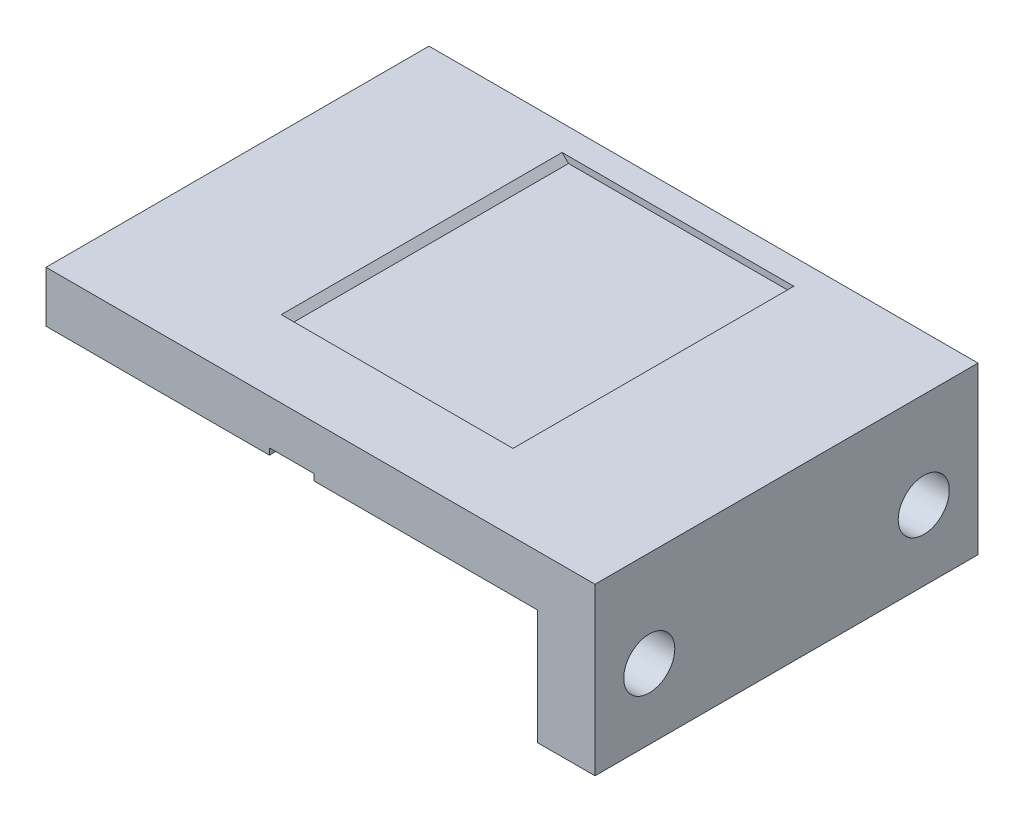
SolidWorks part; units mm, degrees
ref_plane "Front Plane" through (0, 0, 0) normal (0, 0, 1) x (1, 0, 0)
ref_plane "Top Plane" through (0, 0, 0) normal (0, 1, 0) x (1, 0, 0)
ref_plane "Right Plane" through (0, 0, 0) normal (1, 0, 0) x (0, 0, -1)
sketch "Sketch1" plane through (0, 0, 0) normal (0, 1, 0) x (1, 0, 0)
  line L1 (0, 0) -> (77, 0)
  line L2 (0, 0) -> (0, 60)
  line L3 (0, 60) -> (77, 60)
  line L4 (77, 0) -> (77, 60)
  dimension "D1" = 77
  dimension "D2" = 60
extrude "Boss-Extrude1" add sketch "Sketch1" along normal blind 8
sketch "Sketch3" plane through (77, 0, 0) normal (1, 0, 0) x (0, 0, -1)
  line L0 (60, 8) -> (60, 0) construction
  line L1 (0, 8) -> (60, 8)
  line L2 (0, 8) -> (0, -18)
  line L3 (0, -18) -> (60, -18)
  line L4 (60, 8) -> (60, -18)
  dimension "D1" = 26
extrude "Boss-Extrude2" add sketch "Sketch3" along normal blind 9 contours L2 L3 L4 L1
sketch "Sketch4" plane through (86, 0, 0) normal (1, 0, 0) x (0, 0, -1)
  line L0 (0, 8) -> (60, 8) construction
  line L1 (30, 8) -> (30, -18) construction
  line L2 (0, -18) -> (60, -18) construction
  line L5 (0, 8) -> (0, -18) construction
  line L6 (17, -7) -> (0, -7) construction
  circle A0 centre (8.5, -7) radius 4
  circle A2 centre (51.5, -7) radius 4
  point P4 (0, 0)
  point P5 (0, 0)
  point P12 (8.5, -7)
  point P18 (8.5, -7)
  dimension "D1" = 8
  dimension "D2" = 15
  dimension "D3" = 21.5
extrude "Cut-Extrude2" cut sketch "Sketch4" against normal through all
sketch "Sketch5" plane through (0, 8, 0) normal (0, 1, 0) x (1, 0, 0)
  line L0 (86, 60) -> (0, 60) construction
  line L1 (25.85, 12) -> (60.15, 12)
  line L2 (25.85, 12) -> (25.85, 56)
  line L3 (25.85, 56) -> (60.15, 56)
  line L4 (60.15, 12) -> (60.15, 56)
  point P4 (43, 56)
  point P7 (43, 60)
  dimension "D1" = 44
  dimension "D2" = 34.3
  dimension "D3" = 4
extrude "recess" cut sketch "Sketch5" against normal blind 1 contours L1 L4 L3 L2
sketch "Sketch6" plane through (0, 0, -56) normal (0, 0, 1) x (1, 0, 0)
  line L0 (25.85, 7) -> (24.85, 8)
  line L1 (25.85, 8) -> (60.15, 8) construction
  line L2 (25.85, 7) -> (25.85, 8) construction
  line L3 (24.85, 8) -> (25.85, 8)
  line L4 (25.85, 8) -> (25.85, 7)
  line L5 (43, 8) -> (43, 7) construction
  line L6 (25.85, 7) -> (60.15, 7) construction
  line L7 (60.15, 8) -> (60.15, 7)
  line L8 (61.15, 8) -> (60.15, 8)
  line L9 (60.15, 7) -> (61.15, 8)
  dimension "D1" = 45
extrude "Angles in recess" cut sketch "Sketch6" along normal up to surface (44 mm away) up to face at (43, 7.5, -12)
ref_plane "Plane1" through (0, 0, -30) normal (0, 0, 1) x (1, 0, 0)
sketch "Sketch7" plane through (0, 0, 0) normal (0, -1, 0) x (1, 0, 0)
  line L0 (77, -60) -> (0, -60) construction
  line L1 (42, -60) -> (35, -60)
  line L2 (42, -60) -> (42, 0)
  line L3 (42, 0) -> (35, 0)
  line L4 (35, -60) -> (35, 0)
  line L5 (0, 0) -> (77, 0) construction
  point P8 (38.5, -60)
  point P9 (38.5, -60)
  dimension "D1" = 7
extrude "where the belt go" cut sketch "Sketch7" against normal blind 1
